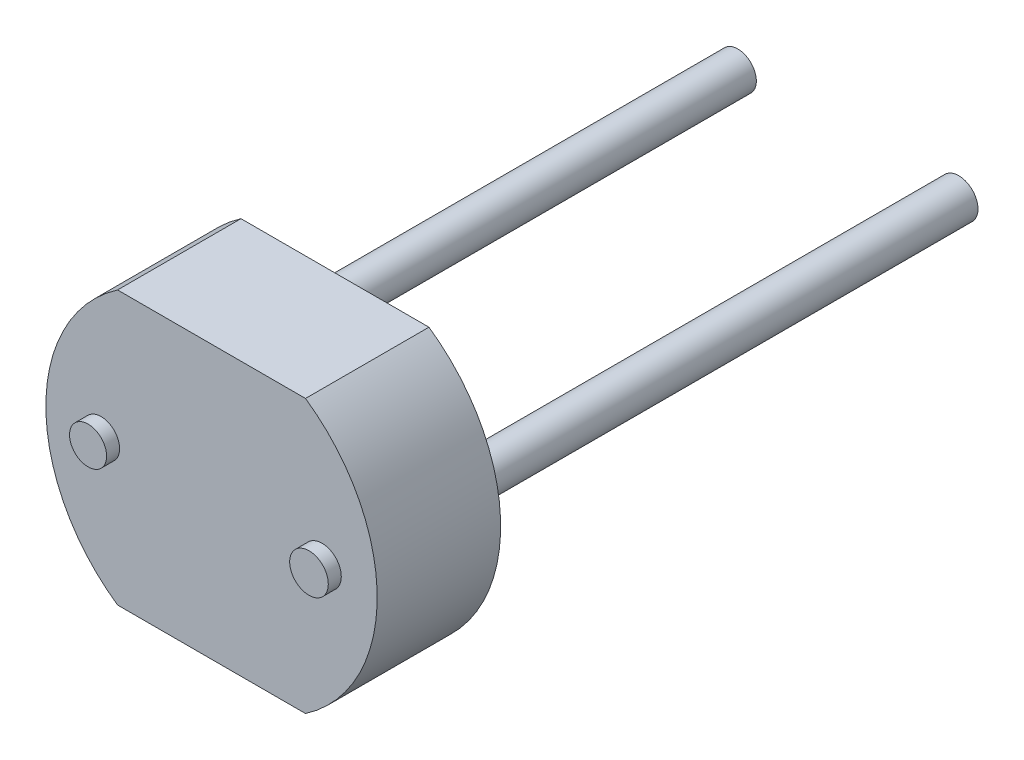
SolidWorks part; units mm, degrees
ref_plane "Plano frontal" through (0, 0, 0) normal (0, 0, 1) x (1, 0, 0)
ref_plane "Plano superior" through (0, 0, 0) normal (0, 1, 0) x (1, 0, 0)
ref_plane "Plano direito" through (0, 0, 0) normal (1, 0, 0) x (0, 0, -1)
sketch "Esboço1" plane through (0, 0, 0) normal (0, 0, 1) x (1, 0, 0)
  line L0 (-1.4465, 1.65) -> (1.4465, 1.65) construction
  line L1 (-1.4465, -2.55) -> (1.4465, -2.55) construction
  line L2 (0, 2.55) -> (0, -0.45) construction
  circle A0 centre (-1.7, -0.45) radius 0.2856 construction
  circle A1 centre (1.7, -0.45) radius 0.2972 construction
  arc A2 (1.4465, -2.55) -> (1.4465, 1.65) centre (0, -0.45) ccw construction
  arc A3 (-1.4465, 1.65) -> (-1.4465, -2.55) centre (0, -0.45) ccw construction
  point P0 (0, -0.45)
  dimension "D1" = 3.4
sketch "Esboço2" plane through (0, 0, 0) normal (0, 0, 1) x (1, 0, 0)
  line L0 (-1.4465, -2.55) -> (1.4465, -2.55) construction
  line L1 (-1.4465, 1.65) -> (1.4465, 1.65) construction
  line L2 (-1.4465, -2.55) -> (1.4465, -2.55)
  line L3 (-1.4465, 1.65) -> (1.4465, 1.65)
  arc A0 (1.4465, -2.55) -> (1.4465, 1.65) centre (0, -0.45) ccw construction
  arc A1 (-1.4465, 1.65) -> (-1.4465, -2.55) centre (0, -0.45) ccw construction
  arc A2 (1.4465, -2.55) -> (1.4465, 1.65) centre (0, -0.45) ccw
  arc A3 (-1.4465, 1.65) -> (-1.4465, -2.55) centre (0, -0.45) ccw
extrude "Ressalto-extrusão1" add sketch "Esboço2" along normal blind 1.9
ref_plane "Plano1" through (0, 0, 2.1) normal (0, 0, 1) x (1, 0, 0)
sketch "Esboço3" plane through (0, 0, 2.1) normal (0, 0, 1) x (1, 0, 0)
  circle A0 centre (1.7, -0.45) radius 0.2972 construction
  circle A1 centre (-1.7, -0.45) radius 0.2856 construction
  circle A2 centre (1.7, -0.45) radius 0.2972
  circle A3 centre (-1.7, -0.45) radius 0.2856
extrude "Ressalto-extrusão2" add sketch "Esboço3" against normal blind 10
